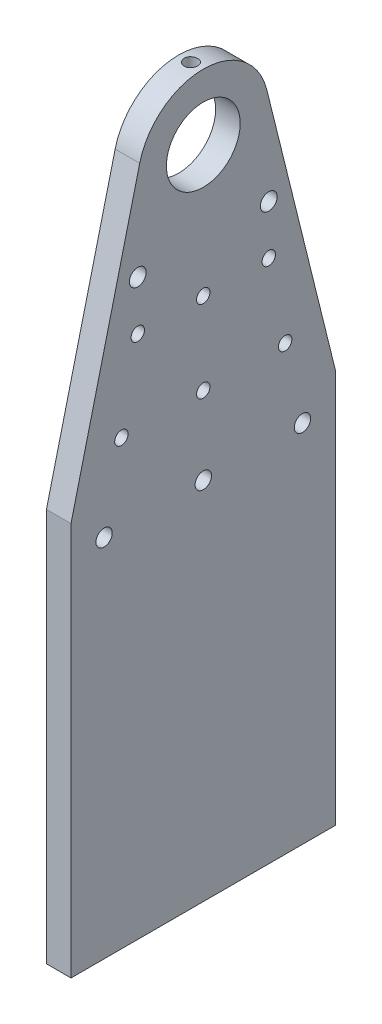
SolidWorks part; units mm, degrees
ref_plane "Front Plane" through (0, 0, 0) normal (0, 0, 1) x (1, 0, 0)
ref_plane "Top Plane" through (0, 0, 0) normal (0, 1, 0) x (1, 0, 0)
ref_plane "Right Plane" through (0, 0, 0) normal (1, 0, 0) x (0, 0, -1)
ref_plane "Plane1" through (-47.625, 0, 0) normal (1, 0, 0) x (0, 0, -1)
sketch "Sketch2" plane through (-47.625, 0, 0) normal (1, 0, 0) x (0, 0, -1)
  line L0 (-51.3017, 52.8) -> (-51.3017, 66.8)
  line L1 (51.3017, 66.8) -> (51.3017, 52.8)
  line L2 (51.3017, 66.8) -> (51.3017, 52.8) construction
  line L3 (-51.3017, 52.8) -> (-51.3017, 66.8) construction
  line L4 (51.3017, -52.8) -> (51.3017, -66.8)
  line L5 (-51.3017, -66.8) -> (-51.3017, -52.8)
  line L6 (-51.3017, -66.8) -> (-51.3017, -52.8) construction
  line L7 (51.3017, -52.8) -> (51.3017, -66.8) construction
  line L8 (0, 0) -> (0, 187.45) construction
  line L15 (51.3017, 73.15) -> (51.3017, 85.85)
  line L16 (-51.3017, -66.8) -> (51.3017, -66.8)
  line L17 (-51.3017, -66.8) -> (-51.3017, 73.15)
  line L18 (-51.3017, 73.15) -> (51.3017, 73.15) construction
  line L19 (51.3017, -66.8) -> (51.3017, 73.15)
  line L20 (51.3017, 85.85) -> (24.6566, 193.5501)
  line L21 (-51.3017, 85.85) -> (-24.6566, 193.5501)
  line L23 (-51.3017, 73.15) -> (-51.3017, 85.85)
  circle A0 centre (0, 187.45) radius 14.3129
  arc A1 (24.6566, 193.5501) -> (-24.6566, 193.5501) centre (0, 187.45) ccw
  circle A8 centre (38.4762, 74.7375) radius 3.175
  circle A9 centre (0, 74.7375) radius 3.175
  circle A10 centre (-38.4762, 74.7375) radius 3.175
  circle A11 centre (-25.4, 136.65) radius 3.175 construction
  circle A12 centre (-31.75, 104.9) radius 3.175 construction
  circle A13 centre (0, 136.65) radius 3.175 construction
  circle A14 centre (0, 104.9) radius 3.175 construction
  circle A15 centre (31.75, 104.9) radius 3.175 construction
  circle A16 centre (-25.4, 136.65) radius 3.175 construction
  circle A17 centre (-31.75, 104.9) radius 3.175 construction
  circle A18 centre (0, 136.65) radius 3.175 construction
  circle A19 centre (0, 104.9) radius 3.175 construction
  circle A20 centre (31.75, 104.9) radius 3.175 construction
  circle A21 centre (0, 136.65) radius 2.6035
  circle A22 centre (-25.4, 136.65) radius 2.6035
  circle A23 centre (-31.75, 104.9) radius 2.6035
  circle A24 centre (0, 104.9) radius 2.6035
  circle A25 centre (31.75, 104.9) radius 2.6035
  circle A26 centre (25.4, 136.65) radius 2.6035
  circle A27 centre (-25.4, 155.7) radius 3.2639
  circle A28 centre (25.4, 155.7) radius 3.2639
  circle A29 centre (38.4762, 74.7375) radius 2.6035 construction
  circle A30 centre (0, 74.7375) radius 2.6035 construction
  circle A31 centre (-38.4762, 74.7375) radius 2.6035 construction
  circle A32 centre (38.4762, 74.7375) radius 2.6035 construction
  circle A33 centre (0, 74.7375) radius 2.6035 construction
  circle A34 centre (-38.4762, 74.7375) radius 2.6035 construction
  dimension "D1" = 28.6258
  dimension "D2" = 25.4
  dimension "D6" = 6.35
  dimension "D7" = 5.207
  dimension "D8" = 6.5278
  dimension "D3" = 6.35
  dimension "D4" = 114.3
  dimension "D5" = 12.7
  dimension "D9" = 25.4
  dimension "D10" = 31.75
extrude "Boss-Extrude1" add sketch "Sketch2" along normal blind 9.525
chamfer "Chamfer1" distance 4.7625 3 edges at (-47.625, 74.7375, -3.175) (-47.625, 74.7375, -41.6512) (-47.625, 74.7375, 35.3012)
sketch "Sketch3" plane through (0, -66.8, 0) normal (0, -1, 0) x (1, 0, 0)
  line L0 (-47.625, 0) -> (-38.1, 0) construction
  line L1 (-47.625, 0) -> (-38.1, -51.3017) construction
  line L2 (-42.8625, -25.6508) -> (-42.8625, -51.3017) construction
  line L4 (-47.625, 51.3017) -> (-47.625, -51.3017)
  line L5 (-47.625, -51.3017) -> (-38.1, -51.3017)
  line L6 (-38.1, -51.3017) -> (-38.1, 51.3017)
  line L7 (-38.1, 51.3017) -> (-47.625, 51.3017)
  line L8 (-47.625, 51.3017) -> (-47.625, -51.3017) construction
  line L9 (-47.625, -51.3017) -> (-38.1, -51.3017) construction
  line L10 (-38.1, -51.3017) -> (-38.1, 51.3017) construction
  line L11 (-38.1, 51.3017) -> (-47.625, 51.3017) construction
  circle A0 centre (-42.8625, -38.4762) radius 2.6035
  circle A1 centre (-42.8625, 0) radius 2.6035
  circle A2 centre (-42.8625, 38.4762) radius 2.6035
  dimension "D2" = 5.207
  dimension "D1" = 0
extrude "Cut-Extrude1" cut sketch "Sketch3" against normal blind 25.4
ref_plane "Plane2" through (0, 212.85, 0) normal (0, 1, 0) x (-1, 0, 0)
sketch "Sketch4" plane through (0, 212.85, 0) normal (0, 1, 0) x (-1, 0, 0)
  line L4 (47.625, 0) -> (38.1, 0)
  line L5 (47.625, 0) -> (38.1, 0) construction
  circle A0 centre (42.8625, 0) radius 2.6035
  dimension "D1" = 5.207
extrude "Cut-Extrude2" cut sketch "Sketch4" against normal up to surface (11.3259 mm away)
